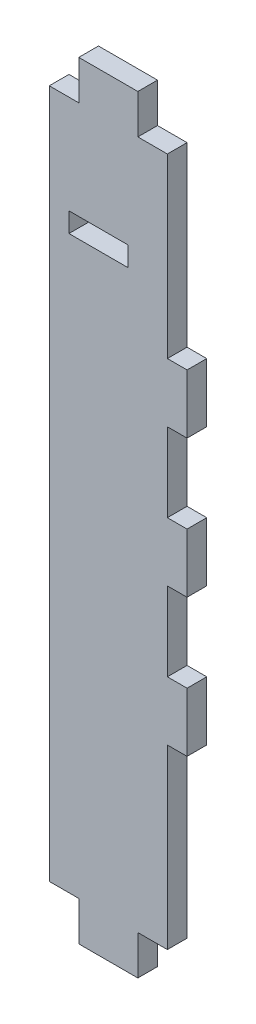
SolidWorks part; units mm, degrees
ref_plane "Front Plane" through (0, 0, 0) normal (0, 0, 1) x (1, 0, 0)
ref_plane "Top Plane" through (0, 0, 0) normal (0, 1, 0) x (1, 0, 0)
ref_plane "Right Plane" through (0, 0, 0) normal (1, 0, 0) x (0, 0, -1)
sketch "Sketch1" plane through (0, 0, 0) normal (0, 0, 1) x (1, 0, 0)
  line L0 (400, 342.5) -> (391.8744, 342.5) construction
  line L1 (430, 430) -> (422.5, 430)
  line L2 (430, 430) -> (430, 385)
  line L3 (430, 255) -> (422.5, 255)
  line L4 (400, 430) -> (400, 255)
  line L5 (407.5, 430) -> (400, 430)
  line L7 (422.5, 430) -> (422.5, 440)
  line L8 (422.5, 440) -> (407.5, 440)
  line L9 (407.5, 430) -> (407.5, 440)
  line L10 (415, 430) -> (407.5, 440) construction
  line L11 (422.5, 440) -> (415, 430) construction
  line L12 (422.5, 245) -> (415, 250) construction
  line L13 (415, 250) -> (407.5, 245) construction
  line L14 (407.5, 255) -> (407.5, 245)
  line L15 (422.5, 245) -> (407.5, 245)
  line L16 (422.5, 255) -> (422.5, 245)
  line L17 (407.5, 255) -> (400, 255)
  line L18 (415, 165) -> (415, 152.4773) construction
  line L19 (430, 335) -> (430, 315)
  line L20 (420, 405) -> (405, 405)
  line L21 (420, 405) -> (420, 400)
  line L22 (420, 400) -> (405, 400)
  line L23 (405, 405) -> (405, 400)
  line L24 (430, 350) -> (435, 350)
  line L26 (430, 335) -> (435, 335)
  line L27 (435, 350) -> (435, 335)
  line L30 (430, 315) -> (435, 315)
  line L31 (435, 315) -> (435, 300)
  line L32 (430, 300) -> (435, 300)
  line L33 (430, 350) -> (435, 350)
  line L34 (435, 350) -> (435, 335)
  line L35 (430, 335) -> (435, 335)
  line L36 (430, 385) -> (435, 385)
  line L37 (435, 385) -> (435, 370)
  line L38 (430, 370) -> (435, 370)
  line L39 (430, 370) -> (430, 350)
  line L40 (430, 300) -> (430, 255)
  point P6 (415, 430)
  point P18 (415, 250)
  point P20 (415, 133.7958)
  point P26 (430, 102.5)
  point P28 (407.5, 255)
  dimension "D1" = 30
  dimension "D2" = 7.5
  dimension "D3" = 15
  dimension "D4" = 10
  dimension "D5" = 5
  dimension "D6" = 10
  dimension "D7" = 15
  dimension "D8" = 25
  dimension "D9" = 15
  dimension "D10" = 5
  dimension "D13" = 97.5
  dimension "D14" = 10
  dimension "D11" = 2
  dimension "D12" = 2
extrude "Boss-Extrude1" add sketch "Sketch1" against normal mid plane 5 contours L40 L32 L31 L30 L19 L26 L27 L24 L39 L38 L37 L36 L2 L1 L7 L8 L9 L5 L4 L17 L14 L15 L16 L3 L23 L20 L21 L22
